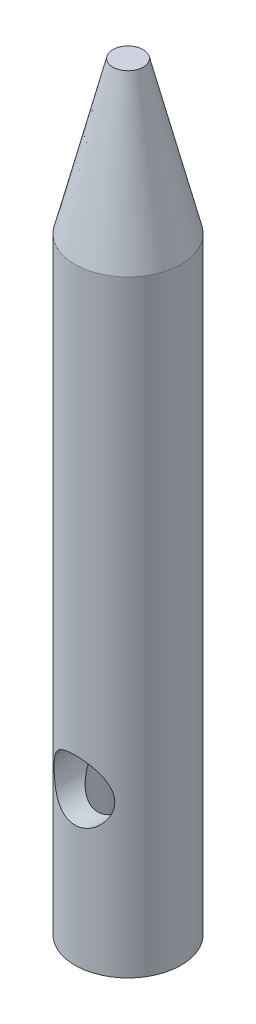
SolidWorks part; units mm, degrees
material "Phosphor bronze 10% D, UNS C52400"
ref_plane "Ön Düzlem" through (0, 0, 0) normal (0, 0, 1) x (1, 0, 0)
ref_plane "Üst Düzlem" through (0, 0, 0) normal (0, 1, 0) x (1, 0, 0)
ref_plane "Sağ Düzlem" through (0, 0, 0) normal (1, 0, 0) x (0, 0, -1)
ref_axis "Axis1" through (0, 0, 0) along (0, 1, 0)
sketch "Sketch1" plane through (0, 0, 0) normal (0, 0, 1) x (1, 0, 0)
  line L0 (-0.2, 0) -> (-0.2, 2)
  line L1 (-0.2, 2) -> (0, 2)
  line L2 (0, 2) -> (0, 5)
  line L3 (0, 5) -> (-0.1, 5)
  line L4 (-0.1, 5) -> (-0.35, 4)
  line L5 (-0.35, 4) -> (-0.35, 0)
  line L6 (-0.35, 0) -> (-0.2, 0)
  dimension "D1" = 0.2
  dimension "D2" = 0.35
  dimension "D3" = 2
  dimension "D4" = 5
  dimension "D5" = 4
  dimension "D6" = 0.1
revolve "Revolve1" add sketch "Sketch1" angle 360 about axis through (0, 0, 0) along (0, 1, 0)
sketch "Sketch2" plane through (0, 0, 0) normal (0, 0, 1) x (1, 0, 0)
  circle A0 centre (0, 1) radius 0.2
  dimension "D1" = 0.4
  dimension "D2" = 1
extrude "Cut-Extrude1" cut sketch "Sketch2" against normal mid plane 10
